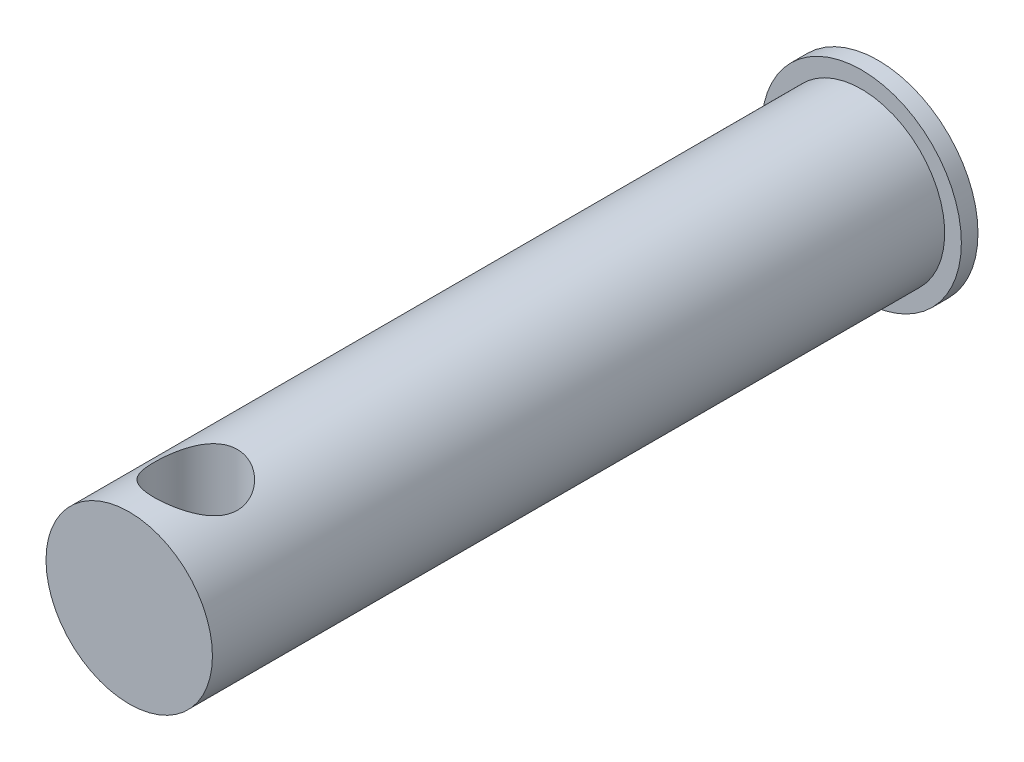
SolidWorks part; units mm, degrees
material "Alumina"
ref_plane "Front Plane" through (0, 0, 0) normal (0, 0, 1) x (1, 0, 0)
ref_plane "Top Plane" through (0, 0, 0) normal (0, 1, 0) x (1, 0, 0)
ref_plane "Right Plane" through (0, 0, 0) normal (1, 0, 0) x (0, 0, -1)
sketch "Sketch3" plane through (0, 0, 0) normal (0, 0, 1) x (1, 0, 0)
  circle A0 centre (0, 0) radius 1.27
  dimension "D1" = 2.54
extrude "Boss-Extrude1" add sketch "Sketch3" along normal mid plane 11.43
sketch "Sketch4" plane through (0, 0, 0) normal (0, 1, 0) x (1, 0, 0)
  line L0 (0, -5.715) -> (0, -4.699) construction
  line L1 (-1.27, -5.715) -> (1.27, -5.715) construction
  circle A0 centre (0, -4.699) radius 0.635
  dimension "D1" = 1.27
  dimension "D2" = 1.016
extrude "Cut-Extrude1" cut sketch "Sketch4" against normal mid plane 3.048
sketch "Sketch5" plane through (0, 0, -5.715) normal (0, 0, -1) x (-1, 0, 0)
  circle A0 centre (0, 0) radius 1.524
  circle A1 centre (0, 0) radius 1.27
  dimension "D1" = 3.048
  dimension "D2" = 2.54
extrude "Boss-Extrude2" add sketch "Sketch5" against normal blind 0.254
